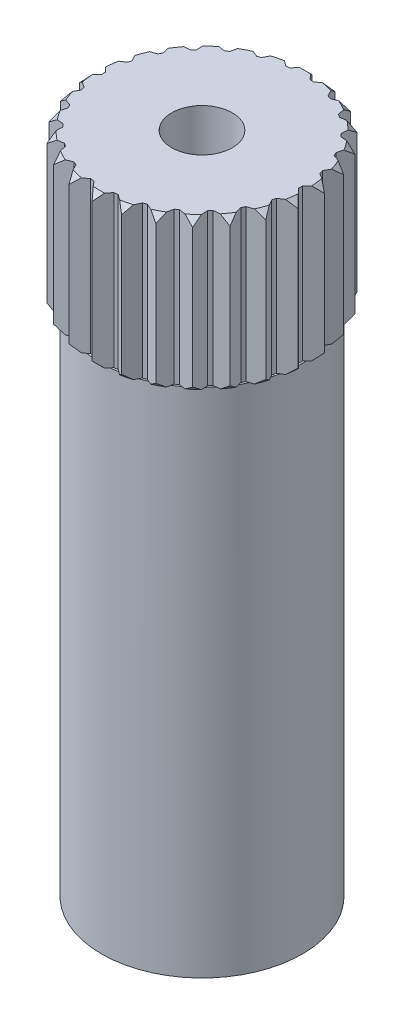
SolidWorks part; units mm, degrees
material "Brass"
ref_plane "Front Plane" through (0, 0, 0) normal (0, 0, 1) x (1, 0, 0)
ref_plane "Top Plane" through (0, 0, 0) normal (0, 1, 0) x (1, 0, 0)
ref_plane "Right Plane" through (0, 0, 0) normal (1, 0, 0) x (0, 0, -1)
sketch "ShaftS" plane through (0, 0, 0) normal (0, 1, 0) x (1, 0, 0)
  circle A0 centre (0, 0) radius 2.9
  dimension "D1" = 5.8
extrude "SHAFT" add sketch "ShaftS" along normal blind 13.5
sketch "ShaftExtensionS" plane through (0, 13.5, 0) normal (0, 1, 0) x (1, 0, 0)
  circle A0 centre (0, 0) radius 2.6
  circle A1 centre (0, 0) radius 2.9 construction
  dimension "D1" = 0.3
extrude "SHAFT EXTENSION" add sketch "ShaftExtensionS" along normal blind 4
sketch "ToothS" plane through (0, 17.5, 0) normal (0, 1, 0) x (1, 0, 0)
  line L0 (0, 2.6) -> (0, 2.9) construction
  line L1 (0, 2.9) -> (-0.2629, 2.5867)
  line L2 (0, 2.9) -> (0.2629, 2.5867)
  line L3 (-0.2629, 2.5867) -> (0.2629, 2.5867) construction
  arc A0 (0.2629, 2.5867) -> (-0.2629, 2.5867) centre (0, 0) ccw
  circle A3 centre (0, 0) radius 2.6 construction
  circle A4 centre (0, 0) radius 2.9 construction
  dimension "D1" = 80
  dimension "D2" = 0.5258
  dimension "D3" = 0.3
extrude "TOOTH" add sketch "ToothS" against normal up to body
pattern_circular "TOOTH CP" count 26 over 360 about axis through (0, 0, 0) along (0, 1, 0) of "TOOTH"
sketch "SmallBoreS" plane through (0, 17.5, 0) normal (0, 1, 0) x (1, 0, 0)
  circle A0 centre (0, 0) radius 0.8
  dimension "D1" = 1.6
extrude "SMALL BORE" cut sketch "SmallBoreS" against normal blind 4
sketch "ShaftUnderCutS" plane through (0, 0, 0) normal (0, 0, 1) x (1, 0, 0)
  line L0 (2.9, 0) -> (2.65, 0)
  line L1 (2.65, 0) -> (2.65, 13.5)
  line L2 (2.65, 13.5) -> (2.9, 13.5)
  line L3 (2.9, 13.5) -> (2.9, 0)
  line L4 (0, 0) -> (2.65, 0) construction
  line L5 (2.7115, 13.5) -> (2.3867, 13.5) construction
  line L6 (0, 13.5) -> (0, 0) construction
  dimension "D1" = 0.25
  dimension "D2" = 2.65
  dimension "D3" = 2.9
revolve "SHAFT UNDER CUT" cut sketch "ShaftUnderCutS" angle 360 about axis through (0, 13.5, 0) along (0, -1, 0)
sketch "TeethChamferS" plane through (0, 0, 0) normal (1, 0, 0) x (0, 0, -1)
  line L0 (2.9, 17.3232) -> (2.9, 17.5)
  line L1 (2.9, 17.5) -> (2.7232, 17.5)
  line L2 (2.7232, 17.5) -> (2.9, 17.3232)
  line L3 (2.9, 13.5) -> (2.9, 17.5) construction
  line L4 (2.9, 15.5) -> (0, 15.5) construction
  line L5 (0, 17.5) -> (0, 13.5) construction
  line L6 (2.7232, 13.5) -> (2.9, 13.6768)
  line L7 (2.9, 13.5) -> (2.7232, 13.5)
  line L8 (2.9, 13.6768) -> (2.9, 13.5)
  point P4 (2.9, 15.5)
  dimension "D1" = 45
  dimension "D2" = 0.25
revolve "TEETH CHAMFER" cut sketch "TeethChamferS" angle 360 about axis through (0, 13.5, 0) along (0, 1, 0)
